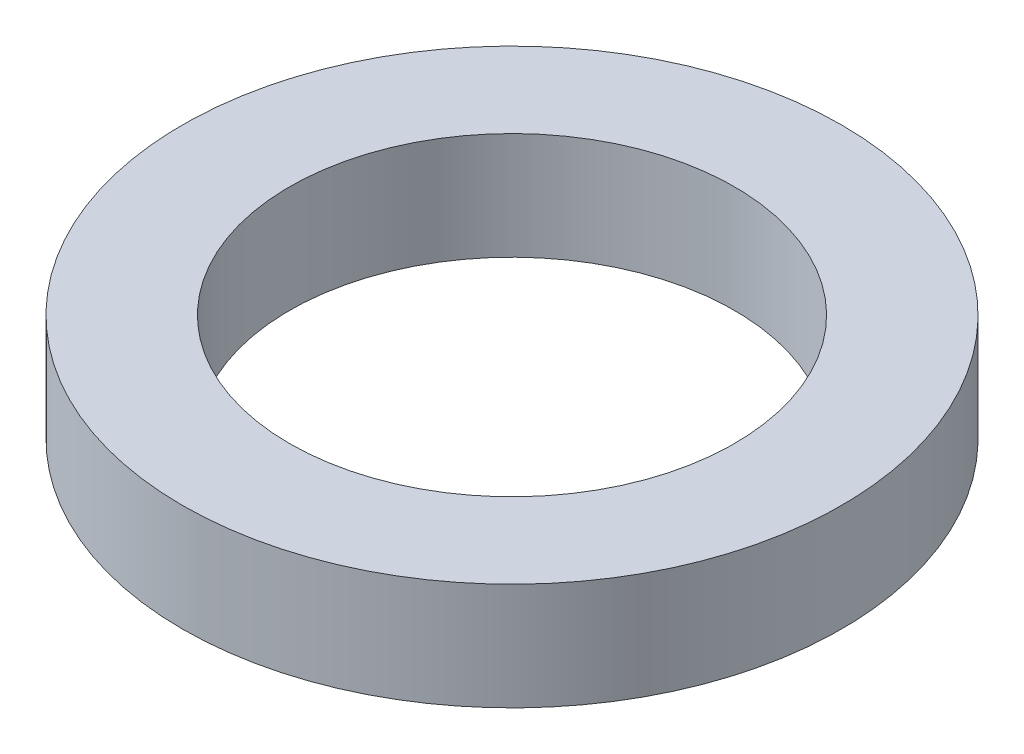
SolidWorks part; units mm, degrees
ref_plane "前视基准面" through (0, 0, 0) normal (0, 0, 1) x (1, 0, 0)
ref_plane "上视基准面" through (0, 0, 0) normal (0, 1, 0) x (1, 0, 0)
ref_plane "右视基准面" through (0, 0, 0) normal (1, 0, 0) x (0, 0, -1)
sketch "草图1" plane through (0, 0, 0) normal (0, 1, 0) x (1, 0, 0)
  circle A0 centre (0, 0) radius 2.7
  circle A2 centre (0, 0) radius 4
  dimension "D1" = 1.3
extrude "凸台-拉伸1" add sketch "草图1" along normal blind 1.3
